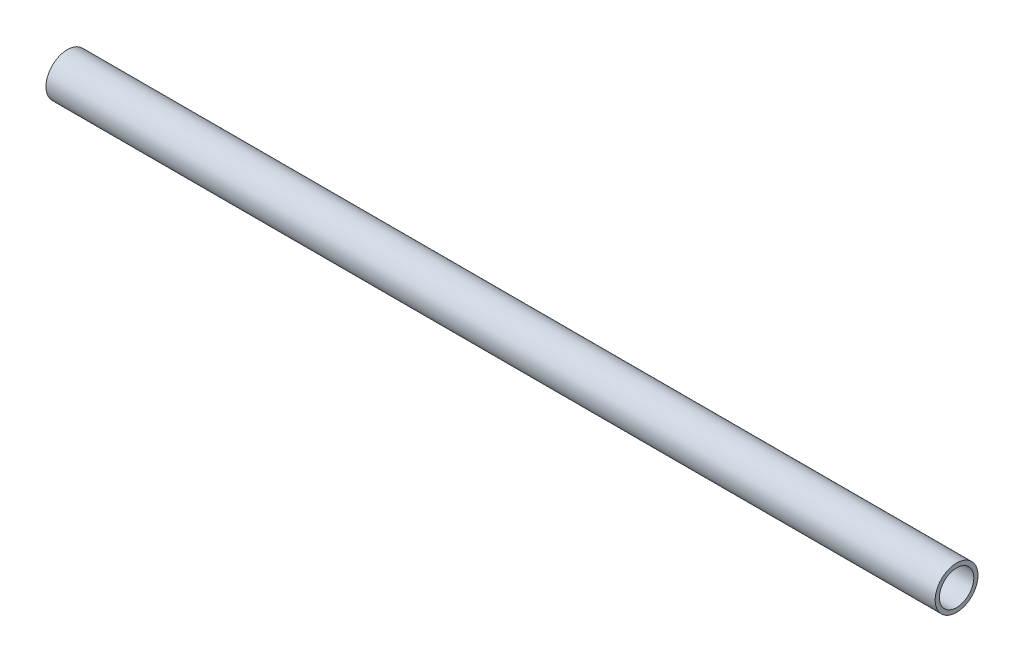
SolidWorks part; units mm, degrees
ref_plane "Vorne" through (0, 0, 0) normal (0, 0, 1) x (1, 0, 0)
ref_plane "Oben" through (0, 0, 0) normal (0, 1, 0) x (1, 0, 0)
ref_plane "Seite" through (0, 0, 0) normal (1, 0, 0) x (0, 0, -1)
sketch "Skizze1" plane through (0, 0, 0) normal (1, 0, 0) x (0, 0, -1)
  circle A0 centre (0, 0) radius 2.55
  circle A1 centre (0, 0) radius 2.05
  dimension "D1" = 4.1
  dimension "D2" = 5.1
extrude "Aufsatz-Linear austragen1" add sketch "Skizze1" along normal mid plane 105.9
